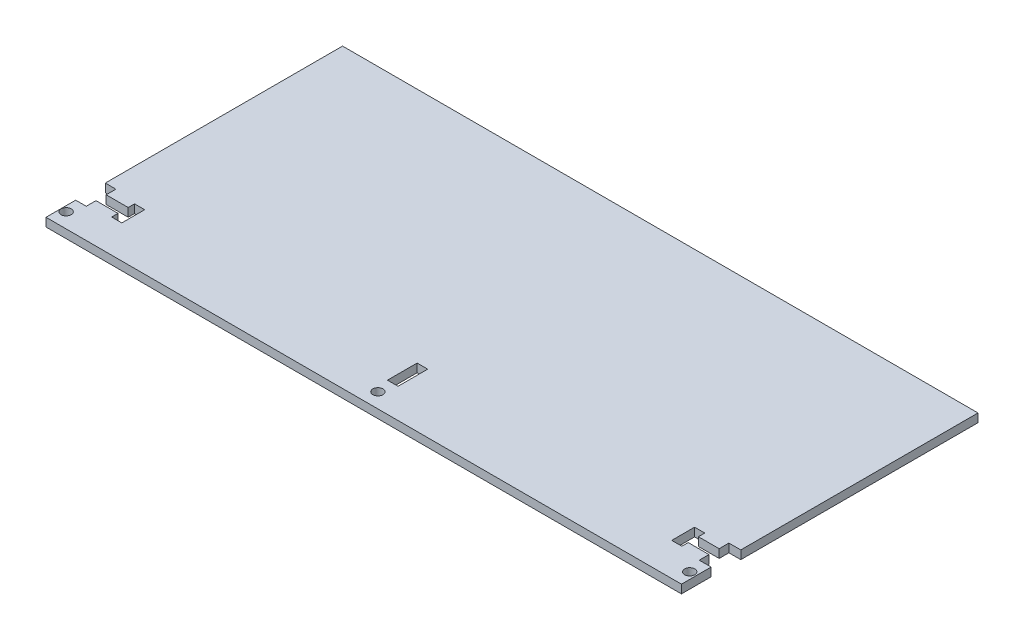
SolidWorks part; units mm, degrees
material "Acrylic (Medium-high impact)"
ref_plane "Front" through (0, 0, 0) normal (0, 0, 1) x (1, 0, 0)
ref_plane "Top" through (0, 0, 0) normal (0, 1, 0) x (1, 0, 0)
ref_plane "Right" through (0, 0, 0) normal (1, 0, 0) x (0, 0, -1)
sketch "Sketch1" plane through (0, 0, 0) normal (0, 1, 0) x (1, 0, 0)
  line L0 (95.25, 0) -> (95.25, -88.9) construction
  line L1 (0, 0) -> (190.5, 0)
  line L2 (0, 0) -> (0, -88.9)
  line L3 (0, -88.9) -> (190.5, -88.9)
  line L4 (190.5, 0) -> (190.5, -88.9)
  line L5 (0, -71.12) -> (3.175, -71.12)
  line L6 (0, -71.12) -> (0, -80.01)
  line L7 (0, -80.01) -> (3.175, -80.01)
  line L8 (3.175, -71.12) -> (3.175, -80.01)
  line L9 (3.175, -74.041) -> (12.827, -74.041)
  line L10 (3.175, -74.041) -> (3.175, -77.089)
  line L11 (3.175, -77.089) -> (12.827, -77.089)
  line L12 (12.827, -74.041) -> (12.827, -77.089)
  line L13 (9.779, -72.136) -> (12.827, -72.136)
  line L14 (9.779, -72.136) -> (9.779, -78.994)
  line L15 (9.779, -78.994) -> (12.827, -78.994)
  line L16 (12.827, -72.136) -> (12.827, -78.994)
  line L17 (177.673, -72.136) -> (177.673, -78.994)
  line L18 (180.721, -78.994) -> (177.673, -78.994)
  line L19 (180.721, -72.136) -> (180.721, -78.994)
  line L20 (180.721, -72.136) -> (177.673, -72.136)
  line L21 (177.673, -74.041) -> (177.673, -77.089)
  line L22 (187.325, -77.089) -> (177.673, -77.089)
  line L23 (187.325, -74.041) -> (187.325, -77.089)
  line L24 (187.325, -74.041) -> (177.673, -74.041)
  line L25 (187.325, -71.12) -> (187.325, -80.01)
  line L26 (190.5, -80.01) -> (187.325, -80.01)
  line L27 (190.5, -71.12) -> (187.325, -71.12)
  line L31 (46.736, 0) -> (46.736, -88.9)
  line L32 (93.472, -71.12) -> (96.647, -71.12)
  line L33 (96.647, -71.12) -> (96.647, -80.01)
  line L34 (93.472, -80.01) -> (96.647, -80.01)
  line L35 (93.472, 0) -> (93.472, -88.9)
  line L39 (140.208, 0) -> (140.208, -88.9)
  line L40 (186.944, -71.12) -> (190.119, -71.12)
  line L41 (190.119, -71.12) -> (190.119, -80.01)
  line L42 (186.944, -80.01) -> (190.119, -80.01)
  line L43 (186.944, 0) -> (186.944, -88.9)
  line L44 (46.736, -71.12) -> (49.911, -71.12) [skipped]
  line L45 (49.911, -71.12) -> (49.911, -80.01) [skipped]
  line L46 (46.736, -80.01) -> (49.911, -80.01) [skipped]
  line L47 (140.208, -80.01) -> (143.383, -80.01) [skipped]
  line L48 (143.383, -71.12) -> (143.383, -80.01) [skipped]
  line L49 (140.208, -71.12) -> (143.383, -71.12) [skipped]
  circle A0 centre (1.5875, -84.455) radius 1.524
  circle A2 centre (95.0595, -84.455) radius 1.524
  circle A4 centre (188.5315, -84.455) radius 1.524
  circle A5 centre (48.3235, -84.455) radius 1.524 [skipped]
  circle A6 centre (141.7955, -84.455) radius 1.524 [skipped]
  point P13 (12.827, -75.565)
  point P14 (3.175, -75.565)
  point P19 (12.827, -75.565)
  point P36 (1.5875, -80.01)
  dimension "D10" = 3.048
  dimension "D1" = 190.5
  dimension "D2" = 88.9
  dimension "D3" = 8.89
  dimension "D4" = 8.89
  dimension "D5" = 3.175
  dimension "D6" = 9.652
  dimension "D7" = 3.048
  dimension "D8" = 3.048
  dimension "D9" = 6.858
  dimension "D11" = 4.445
  dimension "D12" = 5
extrude "Boss-Extrude1" add sketch "Sketch1" along normal blind 2.54
